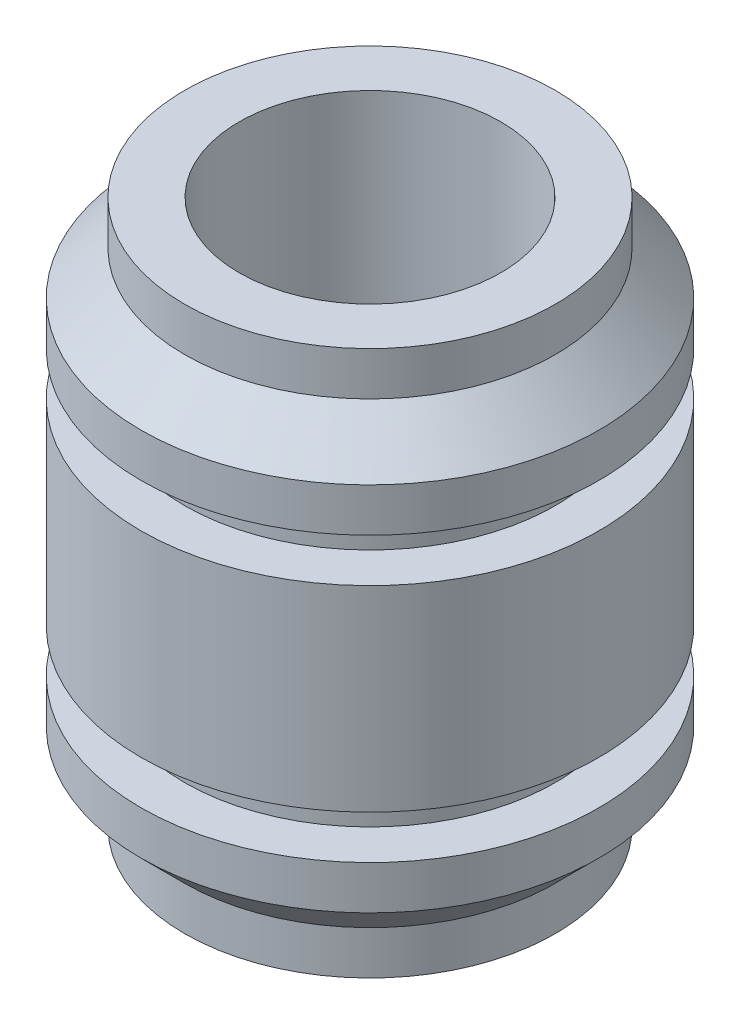
SolidWorks part; units mm, degrees
material "AISI 316 Stainless Steel Sheet (SS)"
ref_plane "Front Plane" through (0, 0, 0) normal (0, 0, 1) x (1, 0, 0)
ref_plane "Top Plane" through (0, 0, 0) normal (0, 1, 0) x (1, 0, 0)
ref_plane "Right Plane" through (0, 0, 0) normal (1, 0, 0) x (0, 0, -1)
sketch "Sketch1" plane through (0, 0, 0) normal (0, 1, 0) x (1, 0, 0)
  circle A0 centre (0, 0) radius 1.05
  circle A1 centre (0, 0) radius 0.6
  dimension "D1" = 2.1
  dimension "D2" = 1.2
extrude "Boss-Extrude1" add sketch "Sketch1" along normal blind 2.5
sketch "Sketch2" plane through (0, 0, 0) normal (1, 0, 0) x (0, 0, -1)
  line L0 (1.05, 1.25) -> (-1.05, 1.25) construction
  line L1 (1.05, 0) -> (1.05, 2.5) construction
  line L2 (-0.85, 1.7) -> (-0.85, 1.9)
  line L3 (-1.05, 1.7) -> (-1.05, 1.9)
  line L4 (-1.05, 2.5) -> (-1.05, 0) construction
  line L5 (-1.05, 2.5) -> (-0.85, 2.5)
  line L6 (-1.05, 2.1) -> (-1.05, 2.5)
  line L7 (-0.85, 0.6) -> (-1.05, 0.6)
  line L8 (-1.05, 2.5) -> (-1.05, 0) construction
  line L9 (-1.05, 1.7) -> (-0.85, 1.7)
  line L10 (-1.05, 2.5) -> (-1.05, 0) construction
  line L11 (-1.05, 0.4) -> (-0.85, 0.2)
  line L12 (-0.85, 0.2) -> (-0.85, 0)
  line L13 (-1.05, 0) -> (1.05, 0) construction
  line L14 (-0.85, 2.3) -> (-0.85, 2.5)
  line L15 (-1.05, 0.8) -> (-0.85, 0.8)
  line L16 (-1.05, 2.1) -> (-0.85, 2.3)
  line L17 (-1.05, 0.4) -> (-1.05, 0)
  line L18 (-1.05, 0) -> (-0.85, 0)
  line L19 (-1.05, 0.8) -> (-1.05, 0.6)
  line L20 (-0.85, 0.8) -> (-0.85, 0.6)
  line L21 (-0.85, 1.9) -> (-1.05, 1.9)
  dimension "D1" = 0.2
  dimension "D2" = 135
  dimension "D3" = 0.2
  dimension "D4" = 0.2
  dimension "D5" = 0.2
ref_axis "Axis1" through (0, 0, 0) along (0, 1, 0)
revolve "Cut-Revolve1" cut sketch "Sketch2" angle 360 about axis through (0, 0, 0) along (0, 1, 0)
